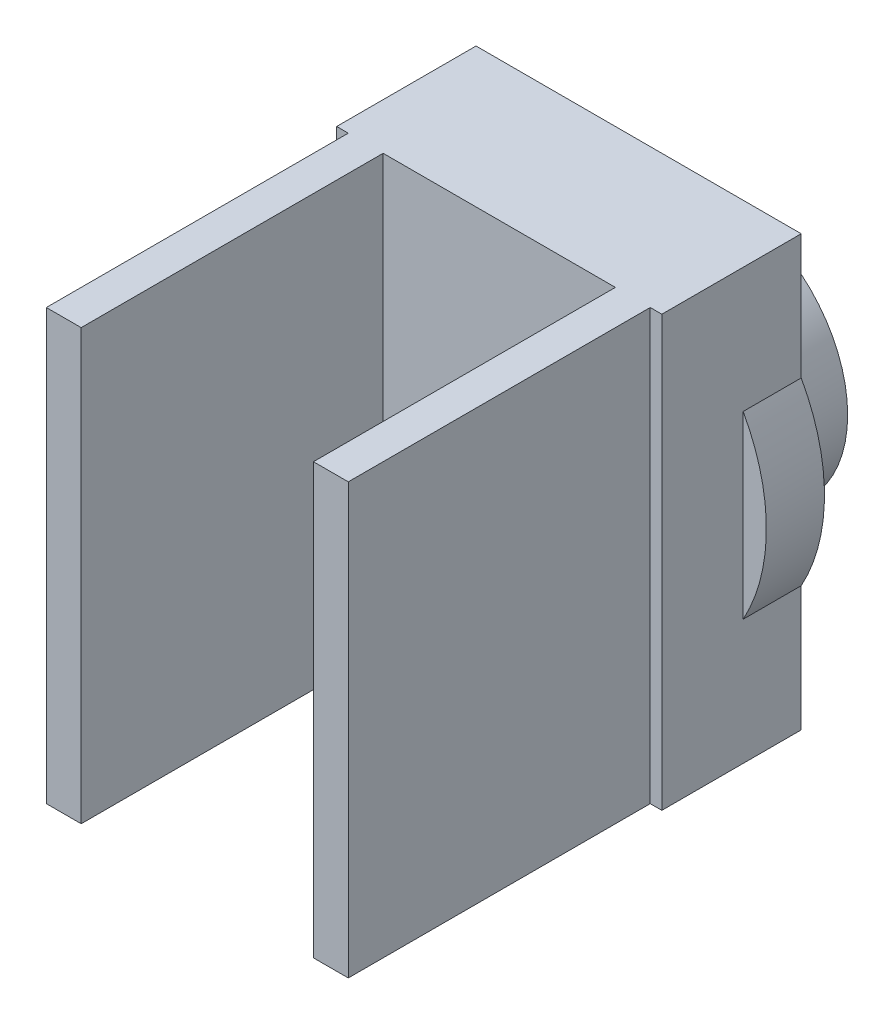
SolidWorks part; units mm, degrees
ref_plane "前视基准面" through (0, 0, 0) normal (0, 0, 1) x (1, 0, 0)
ref_plane "上视基准面" through (0, 0, 0) normal (0, 1, 0) x (1, 0, 0)
ref_plane "右视基准面" through (0, 0, 0) normal (1, 0, 0) x (0, 0, -1)
other "Configuration Table"
sketch "草图1" plane through (0, 0, 0) normal (0, 0, 1) x (1, 0, 0)
  circle A0 centre (0, 0) radius 22
extrude "凸台-拉伸1" add sketch "草图1" against normal blind 14
sketch "草图2" plane through (0, 0, 0) normal (0, 0, 1) x (1, 0, 0)
  circle A0 centre (0, 0) radius 32
extrude "凸台-拉伸2" add sketch "草图2" along normal blind 10
sketch "草图3" plane through (0, 0, 0) normal (0, 0, 1) x (1, 0, 0)
  line L1 (-28, -37) -> (28, -37)
  line L2 (-28, -37) -> (-28, 37)
  line L3 (-28, 37) -> (28, 37)
  line L4 (28, -37) -> (28, 37)
  line L5 (-28, -37) -> (28, 37) construction
  line L6 (-28, 37) -> (28, -37) construction
  point P0 (0, 0)
extrude "凸台-拉伸3" add sketch "草图3" along normal blind 24
sketch "草图4" plane through (0, 0, 0) normal (0, 0, 1) x (1, 0, 0)
  line L0 (28, 37) -> (-28, 37) construction
  line L1 (20, -37) -> (26, -37)
  line L2 (20, -37) -> (20, 37)
  line L3 (20, 37) -> (26, 37)
  line L4 (26, -37) -> (26, 37)
  line L5 (20, -37) -> (26, 37) construction
  line L6 (20, 37) -> (26, -37) construction
  line L8 (-26, -37) -> (-20, -37)
  line L9 (-26, -37) -> (-26, 37)
  line L10 (-26, 37) -> (-20, 37)
  line L11 (-20, -37) -> (-20, 37)
  line L12 (-26, -37) -> (-20, 37) construction
  line L13 (-26, 37) -> (-20, -37) construction
  point P0 (23, 0)
  point P7 (-23, 0)
extrude "凸台-拉伸4" add sketch "草图4" along normal blind 76
